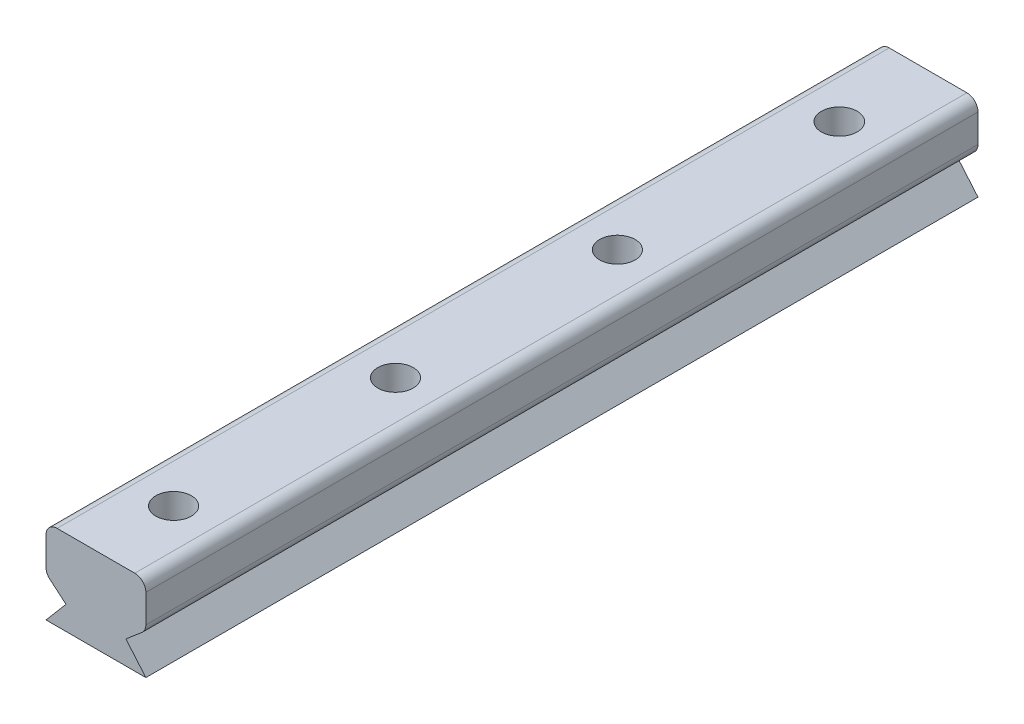
SolidWorks part; units mm, degrees
ref_plane "前视基准面" through (0, 0, 0) normal (0, 0, 1) x (1, 0, 0)
ref_plane "上视基准面" through (0, 0, 0) normal (0, 1, 0) x (1, 0, 0)
ref_plane "右视基准面" through (0, 0, 0) normal (1, 0, 0) x (0, 0, -1)
sketch "草图1" plane through (0, 0, 0) normal (0, 0, 1) x (1, 0, 0)
  line L0 (0, 0) -> (9, 0)
  line L1 (9, 0) -> (9, -4)
  line L2 (9, -4) -> (7.2, -5.5293)
  line L3 (7.2, -5.5293) -> (9, -7.6479)
  line L4 (9, -7.6479) -> (0, -7.6479)
  line L5 (0, -7.6479) -> (1.8, -5.5293)
  line L6 (1.8, -5.5293) -> (0, -4)
  line L7 (0, -4) -> (0, 0)
  dimension "D1" = 9
  dimension "D2" = 9
  dimension "D3" = 4
  dimension "D4" = 1.8
extrude "凸台-拉伸1" add sketch "草图1" along normal blind 75
fillet "圆角1" radius 1 2 edges at (9, 0, 37.5) (0, 0, 37.5)
fillet "圆角2" radius 1 2 edges at (0, -4, 37.5) (9, -4, 37.5)
sketch "草图2" plane through (0, -7.6479, 0) normal (0, -1, 0) x (1, 0, 0)
  line L0 (4.5, 75) -> (4.5, 0) construction
  line L1 (0, 75) -> (9, 75) construction
  line L2 (0, 0) -> (9, 0) construction
  circle A1 centre (4.5, 68) radius 1.6
  circle A2 centre (4.5, 48) radius 1.6
  circle A3 centre (4.5, 28) radius 1.6
  circle A4 centre (4.5, 8) radius 1.6172
  dimension "D1" = 7
  dimension "D2" = 20
  dimension "D3" = 20
  dimension "D4" = 20
  dimension "D5" = 3.2
  dimension "D6" = 3.2
  dimension "D7" = 3.2
extrude "切除-拉伸1" cut sketch "草图2" against normal blind 14
